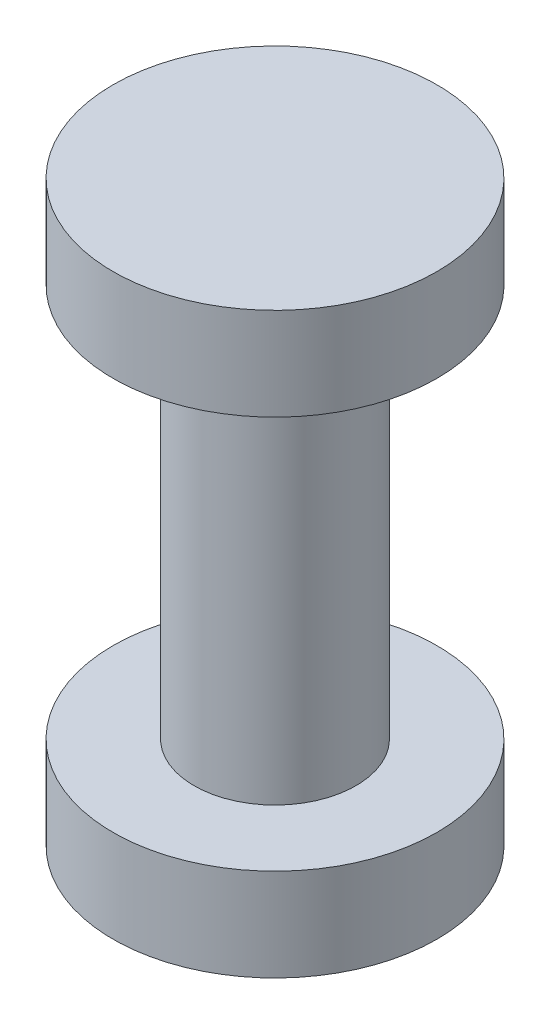
SolidWorks part; units mm, degrees
ref_plane "Front Plane" through (0, 0, 0) normal (0, 0, 1) x (1, 0, 0)
ref_plane "Top Plane" through (0, 0, 0) normal (0, 1, 0) x (1, 0, 0)
ref_plane "Right Plane" through (0, 0, 0) normal (1, 0, 0) x (0, 0, -1)
sketch "Sketch1" plane through (0, 0, 0) normal (0, 0, 1) x (1, 0, 0)
  line L25 (0, 0) -> (1778, 0)
  line L26 (0, 0) -> (0, -1016)
  line L27 (889, -1016) -> (1778, -1016)
  line L28 (1778, 0) -> (1778, -1016)
  line L30 (0, -1016) -> (0, -5334)
  line L32 (889, -1016) -> (889, -5334)
  line L33 (889, -5334) -> (1778, -5334)
  line L34 (0, -5334) -> (0, -6350)
  line L35 (0, -6350) -> (1778, -6350)
  line L36 (1778, -5334) -> (1778, -6350)
  dimension "D1" = 1778
  dimension "D2" = 1016
  dimension "D3" = 889
  dimension "D4" = 4318
  dimension "D5" = 1778
  dimension "D6" = 1016
revolve "Revolve1" add sketch "Sketch1" angle 360 about L30
